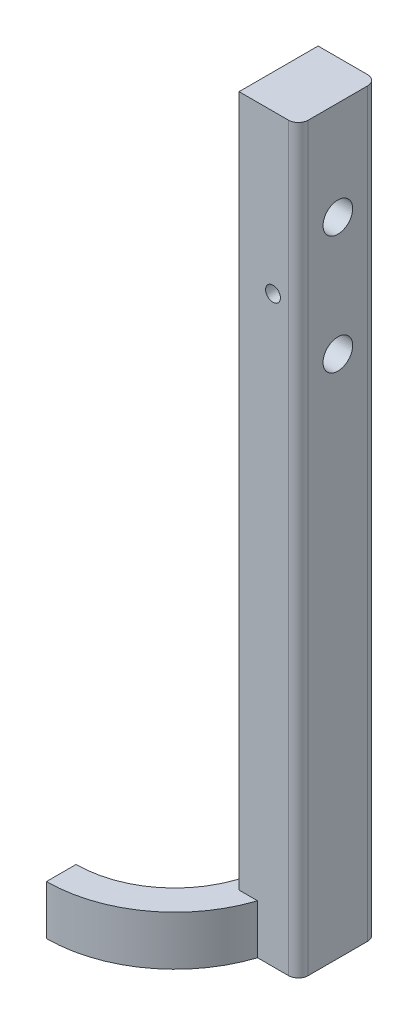
SolidWorks part; units mm, degrees
ref_plane "Front Plane" through (0, 0, 0) normal (0, 0, 1) x (1, 0, 0)
ref_plane "Top Plane" through (0, 0, 0) normal (0, 1, 0) x (1, 0, 0)
ref_plane "Right Plane" through (0, 0, 0) normal (1, 0, 0) x (0, 0, -1)
sketch "Sketch1" plane through (0, 0, 0) normal (0, 1, 0) x (1, 0, 0)
  line L0 (0, 13) -> (0, 10)
  line L1 (0, -10) -> (0, -13)
  arc A0 (0, -10) -> (0, 10) centre (0, 0) ccw
  arc A1 (0, -13) -> (0, 13) centre (0, 0) ccw
  circle A2 centre (0, 0) radius 13 construction
  circle A3 centre (0, 0) radius 10 construction
  dimension "D1" = 20
  dimension "D2" = 3
extrude "Boss-Extrude1" add sketch "Sketch1" along normal blind 5
sketch "Sketch2" plane through (0, 0, 0) normal (0, 1, 0) x (1, 0, 0)
  line L0 (0, 0) -> (16.5, 0) construction
  line L1 (16.5, 4) -> (10.5, 4)
  line L2 (16.5, 4) -> (16.5, -4)
  line L3 (16.5, -4) -> (10.5, -4)
  line L4 (10.5, 4) -> (10.5, -4)
  dimension "D1" = 6
  dimension "D2" = 8
  dimension "D3" = 16.5
extrude "Boss-Extrude2" add sketch "Sketch2" along normal blind 75
fillet "Fillet2" radius 1 2 edges at (16.5, 37.5, -4) (16.5, 37.5, 4)
sketch "Sketch3" plane through (10.5, 0, 0) normal (-1, 0, 0) x (0, 0, 1)
  line L0 (-4, 75) -> (4, 75) construction
  line L1 (4, 5) -> (-4, 5) construction
  circle A0 centre (0, 65) radius 1.5
  circle A1 centre (0, 53) radius 1.5
  point P4 (0, 0)
  point P7 (0, 5)
  dimension "D1" = 3
  dimension "D2" = 10
  dimension "D3" = 12
extrude "Cut-Extrude1" cut sketch "Sketch3" against normal through all
ref_plane "Plane1" through (0, 2.5, 0) normal (0, 1, 0) x (1, 0, 0)
sketch "Sketch4" plane through (0, 2.5, 0) normal (0, 1, 0) x (1, 0, 0)
  line L0 (0, 9) -> (0, 8.5)
  line L1 (0, -8.5) -> (0, -9)
  arc A3 (0, -8.5) -> (0, 8.5) centre (0, 0) ccw
  arc A4 (0, -9) -> (0, 9) centre (0, 0) ccw
  circle A5 centre (0, 0) radius 9 construction
  circle A6 centre (0, 0) radius 8.5 construction
  dimension "D1" = 17
  dimension "D2" = 0.5
extrude "Boss-Extrude3" add sketch "Sketch4" along normal mid plane 1 separate body
loft "Loft1" add section face at (5, 2.5, 0) section face at (4.25, 2.5, 0)
sketch "Sketch6" plane through (0, 0, 4) normal (0, 0, 1) x (1, 0, 0)
  line L0 (10.5, 75) -> (15.5, 75) construction
  line L1 (12.3693, 0) -> (15.5, 0) construction
  circle A0 centre (13.9347, 59) radius 0.75
  point P4 (0, 0)
  point P7 (13.9347, 0)
  dimension "D1" = 1.5
  dimension "D2" = 16
extrude "Cut-Extrude3" cut sketch "Sketch6" against normal through all
equation "\"Inner Diamerter\"= 20mm"
equation "\"Ring Thickness\"= 5mm"
equation "\"D1@Sketch1\"=\"Inner Diamerter\""
equation "\"D1@Sketch4\"=\"Inner Diamerter\" - 3"
